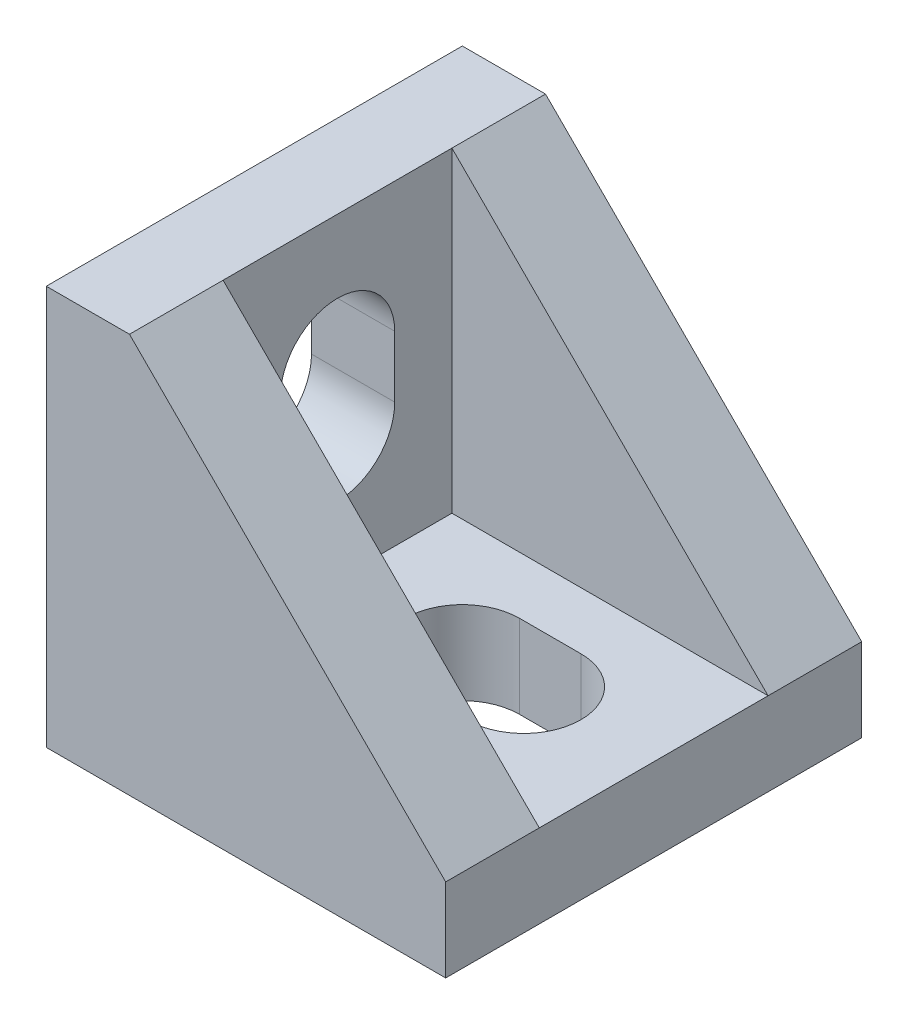
SolidWorks part; units mm, degrees
ref_plane "Front Plane" through (0, 0, 0) normal (0, 0, 1) x (1, 0, 0)
ref_plane "Top Plane" through (0, 0, 0) normal (0, 1, 0) x (1, 0, 0)
ref_plane "Right Plane" through (0, 0, 0) normal (1, 0, 0) x (0, 0, -1)
sketch "Sketch1" plane through (0, 0, 0) normal (0, 0, 1) x (1, 0, 0)
  line L0 (0, 0) -> (0, 19.2)
  line L1 (0, 0) -> (26.7491, 26.7491) construction
  line L2 (0, 19.2) -> (4, 19.2)
  line L3 (4, 19.2) -> (11.6, 11.6)
  line L4 (0, 0) -> (11.6, 11.6)
  dimension "D1" = 45
  dimension "D2" = 19.2
  dimension "D3" = 4
extrude "Boss-Extrude1" add sketch "Sketch1" along normal blind 4.5
sketch "Sketch2" plane through (0, 0, 0) normal (1, 0, 0) x (0, 0, -1)
  line L0 (-4.5, 19.2) -> (-10, 19.2)
  line L1 (-10, 19.2) -> (-10, 15.7)
  line L2 (-10, 0) -> (-4.5, 0)
  line L3 (-10, 4.5) -> (-4.5, 4.5) construction
  line L4 (-4.5, 0) -> (-4.5, 11.6) construction
  line L5 (-10, 15.7) -> (-10, 7.25) construction
  line L6 (-10, 7.25) -> (-10, 0)
  line L7 (-4.5, 19.2) -> (-4.5, 0)
  line L8 (-7.25, 12.95) -> (-7.25, 10)
  arc A1 (-10, 15.7) -> (-7.25, 12.95) centre (-10, 12.95) cw
  arc A2 (-10, 7.25) -> (-7.25, 10) centre (-10, 10) ccw
  dimension "D3" = 2.75
  dimension "D1" = 4.5
  dimension "D2" = 5.5
  dimension "D4" = 5.5
  dimension "D5" = 3.5
extrude "Boss-Extrude2" add sketch "Sketch2" along normal blind 4
mirror "Mirror3" about plane through (4, 19.2, 10) normal (0, 0, -1) of bodies 102
mirror "Mirror4" about plane through (0, 0, 15.5) normal (-0.7071, 0.7071, 0) of bodies 105
equation "\"D3@Sketch2\"=5.5/2"
